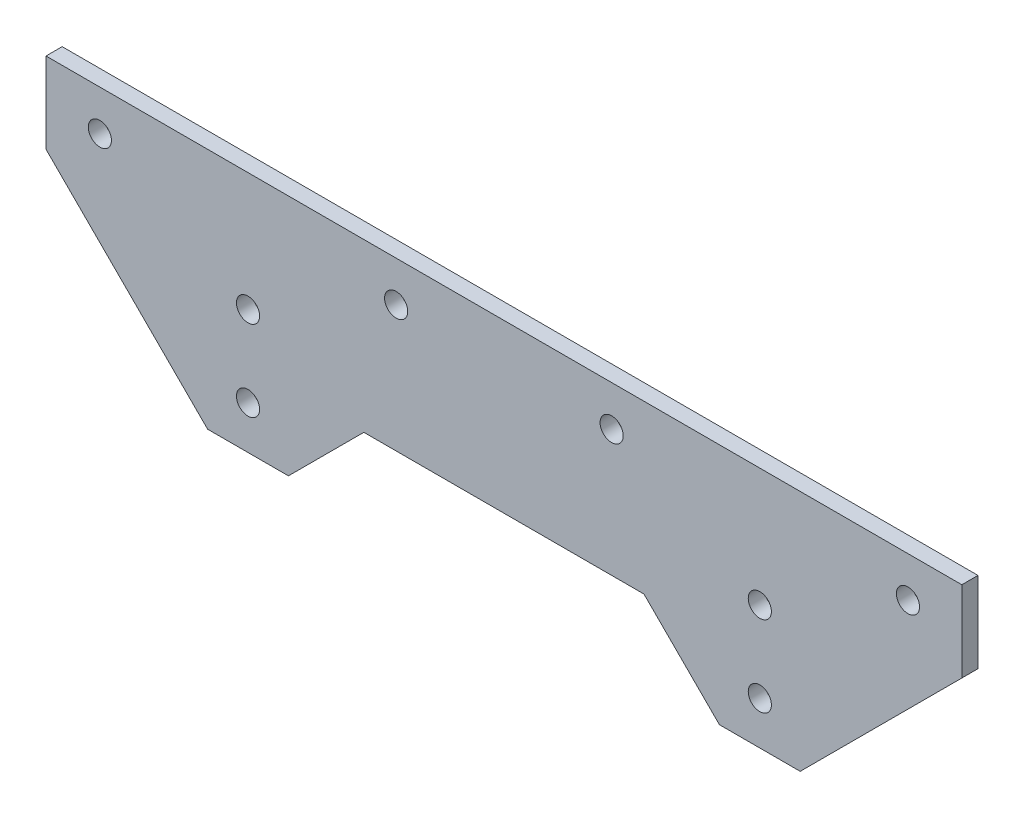
SolidWorks part; units mm, degrees
material "Thornel Mat VMA"
ref_plane "Front Plane" through (0, 0, 0) normal (0, 0, 1) x (1, 0, 0)
ref_plane "Top Plane" through (0, 0, 0) normal (0, 1, 0) x (1, 0, 0)
ref_plane "Right Plane" through (0, 0, 0) normal (1, 0, 0) x (0, 0, -1)
sketch "Sketch1" plane through (0, 0, 0) normal (0, 0, 1) x (1, 0, 0)
  line L0 (-85, 225.9999) -> (-85, 210.9999)
  line L1 (295, 225.9999) -> (-295, 225.9999) construction
  line L2 (-295, 210.9999) -> (-55, 210.9999) construction
  line L3 (-85, 210.9999) -> (-55, 180.9999)
  line L4 (-55, 210.9999) -> (-55, -210.9999) construction
  line L5 (-55, 180.9999) -> (-40, 180.9999)
  line L6 (-40, 210.9999) -> (-40, -210.9999) construction
  line L7 (-40, 180.9999) -> (-26, 194.9999)
  line L8 (-26, 194.9999) -> (26, 194.9999)
  line L9 (26, 194.9999) -> (40, 180.9999)
  line L10 (40, -210.9999) -> (40, 210.9999) construction
  line L11 (40, 180.9999) -> (55, 180.9999)
  line L12 (55, -210.9999) -> (55, 210.9999) construction
  line L13 (55, 180.9999) -> (85, 210.9999)
  line L14 (55, 210.9999) -> (295, 210.9999) construction
  line L15 (85, 210.9999) -> (85, 225.9999)
  line L16 (85, 225.9999) -> (-85, 225.9999)
  line L17 (0, 194.9999) -> (0, 225.9999) construction
  line L18 (40, 210.9999) -> (-40, 210.9999) construction
  line L19 (-85, 218.4999) -> (85, 218.4999) construction
  line L20 (-47.5, 180.9999) -> (-47.5, 225.9999) construction
  line L21 (47.5, 180.9999) -> (47.5, 225.9999) construction
  circle A0 centre (-47.5, 188.9999) radius 2.15
  circle A1 centre (-47.5, 203.9999) radius 2.15
  circle A2 centre (-75, 218.4999) radius 2.15
  circle A3 centre (-20, 218.4999) radius 2.15
  circle A4 centre (47.5, 188.9999) radius 2.15
  circle A5 centre (47.5, 203.9999) radius 2.15
  circle A6 centre (20, 218.4999) radius 2.15
  circle A7 centre (75, 218.4999) radius 2.15
  dimension "D6" = 4.3
  dimension "D7" = 8
  dimension "D8" = 15
  dimension "D9" = 10
  dimension "D10" = 20
  dimension "D1" = 135
  dimension "D2" = 135
  dimension "D3" = 45
  dimension "D4" = 30
  dimension "D5" = 16
extrude "Extrude1" add sketch "Sketch1" along normal blind 3
